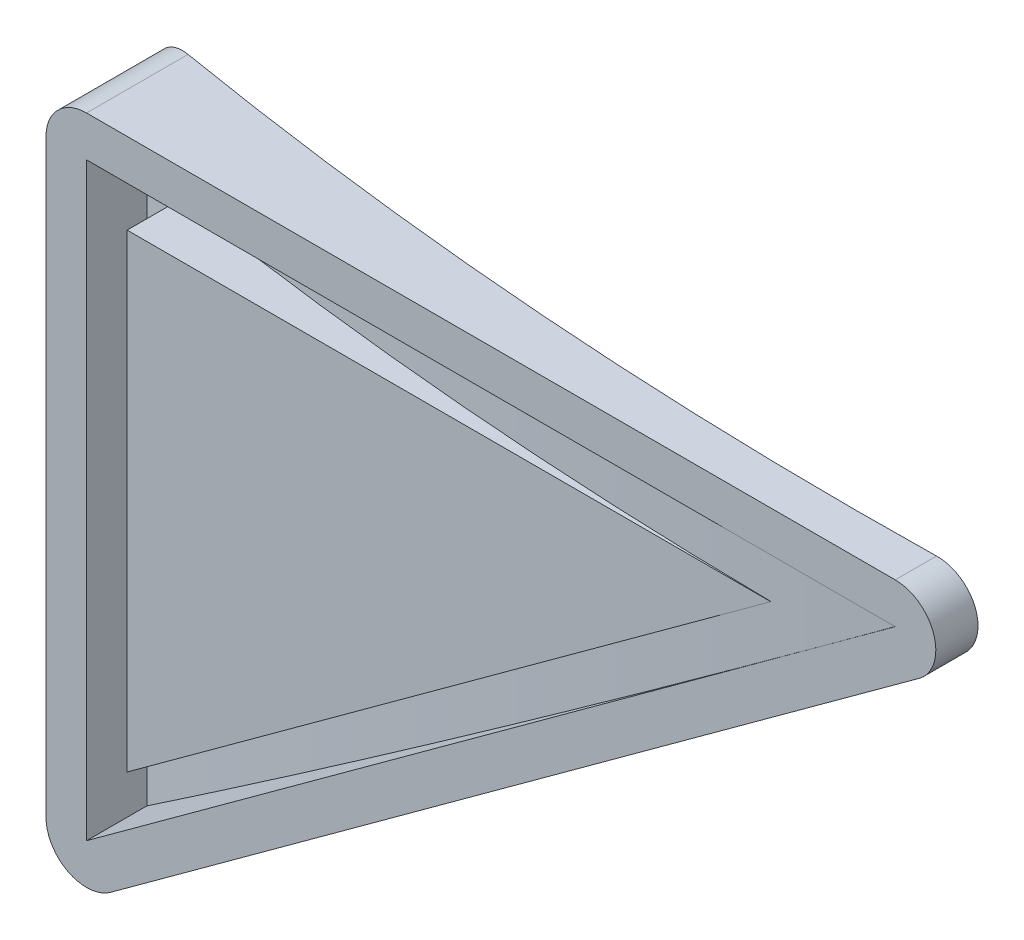
SolidWorks part; units mm, degrees
ref_plane "Front Plane" through (0, 0, 0) normal (0, 0, 1) x (1, 0, 0)
ref_plane "Top Plane" through (0, 0, 0) normal (0, 1, 0) x (1, 0, 0)
ref_plane "Right Plane" through (0, 0, 0) normal (1, 0, 0) x (0, 0, -1)
sketch "Sketch1" plane through (0, 0, 0) normal (0, 1, 0) x (1, 0, 0)
  line L0 (-200, -1068.4423) -> (-200, -1078.6144)
  line L1 (200, -1068.4423) -> (200, -1078.6144)
  arc A0 (-200, -1068.4423) -> (200, -1068.4423) centre (0, 0) ccw
  arc A1 (-200, -1078.6144) -> (200, -1078.6144) centre (0, 0) ccw
  dimension "D1" = 2194
  dimension "D2" = 10
  dimension "D3" = 200
  dimension "D4" = 400
extrude "Boss-Extrude1" add sketch "Sketch1" along normal blind 175
fillet "Fillet1" radius 10 3 edges at (200, 0, 1073.5284) (200, 175, 1073.5284) (-200, 0, 1073.5284)
sketch "Sketch4" plane through (0, 0, 0) normal (0, 0, 1) x (1, 0, 0)
  line L0 (-190, 0) -> (50, 175)
  line L1 (-190, 0) -> (190, 0) construction
  line L2 (190, 175) -> (-200, 175) construction
  line L7 (-200, 175) -> (-200, 10) construction
  line L8 (-190, 0) -> (-190, 175)
  line L9 (-190, 175) -> (50, 175)
  dimension "D1" = 250
extrude "Cut-Extrude3" cut sketch "Sketch4" against normal through all both and the other way through all flip side to cut
fillet "Fillet4" radius 10 3 edges at (50, 175, 1090.8547) (-190, 0, 1075.3433) (-190, 175, 1075.3433)
ref_plane "Plane3" through (0, 0, 1097) normal (0, 0, 1) x (1, 0, 0)
sketch "Sketch5" plane through (0, 0, 1097) normal (0, 0, 1) x (1, 0, 0)
  line L3 (19.3127, 175) -> (-180, 175) construction
  line L4 (-174.1083, 11.5877) -> (25.2045, 156.9199) construction
  line L5 (-190, 165) -> (-190, 19.6678) construction
  line L6 (-180, 165) -> (-180, 19.6678)
  line L7 (-180, 19.6678) -> (19.3127, 165)
  line L8 (19.3127, 165) -> (-180, 165)
  line L9 (-180, 165) -> (-180, 19.6678)
  line L10 (-180, 19.6678) -> (19.3127, 165)
  line L11 (19.3127, 165) -> (-180, 165)
  line L12 (-174.1083, 11.5877) -> (25.2045, 156.9199)
  line L13 (-190, 165) -> (-190, 19.6678)
  line L14 (19.3127, 175) -> (-180, 175)
  arc A3 (25.2045, 156.9199) -> (19.3127, 175) centre (19.3127, 165) ccw construction
  arc A4 (-190, 19.6678) -> (-174.1083, 11.5877) centre (-180, 19.6678) ccw construction
  arc A5 (-180, 175) -> (-190, 165) centre (-180, 165) ccw construction
  arc A6 (25.2045, 156.9199) -> (19.3127, 175) centre (19.3127, 165) ccw
  arc A7 (-190, 19.6678) -> (-174.1083, 11.5877) centre (-180, 19.6678) ccw
  arc A8 (-180, 175) -> (-190, 165) centre (-180, 165) ccw
  dimension "D1" = 10
extrude "Boss-Extrude2" add sketch "Sketch5" against normal up to surface (14.8683 mm away)
sketch "Sketch6" plane through (0, 0, 1097) normal (0, 0, 1) x (1, 0, 0)
  line L10 (-11.3745, 155) -> (-170, 155)
  line L11 (-170, 155) -> (-170, 39.3356)
  line L12 (-170, 39.3356) -> (-11.3745, 155)
  line L13 (-11.3745, 155) -> (-170, 155)
  line L14 (-170, 155) -> (-170, 39.3356)
  line L15 (-170, 39.3356) -> (-11.3745, 155)
  dimension "D1" = 10
extrude "Boss-Extrude3" add sketch "Sketch6" against normal up to surface (13.2523 mm away)
